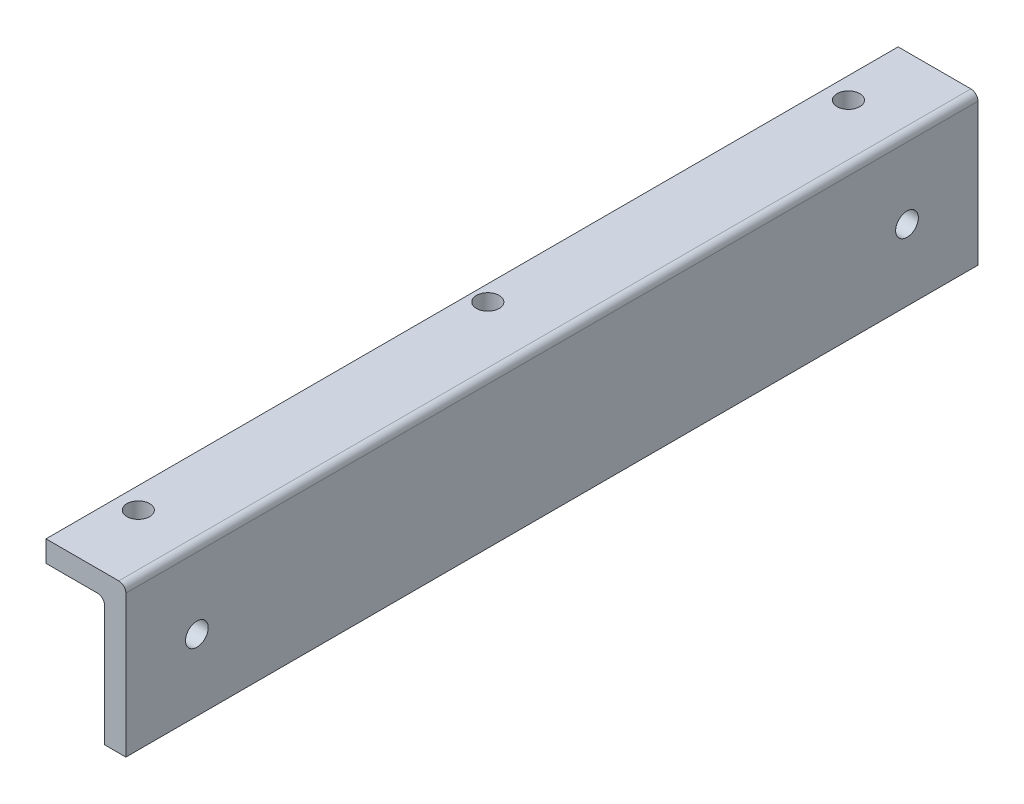
SolidWorks part; units mm, degrees
ref_plane "前视基准面" through (0, 0, 0) normal (0, 0, 1) x (1, 0, 0)
ref_plane "上视基准面" through (0, 0, 0) normal (0, 1, 0) x (1, 0, 0)
ref_plane "右视基准面" through (0, 0, 0) normal (1, 0, 0) x (0, 0, -1)
sketch "草图1" plane through (0, 0, 0) normal (0, 0, 1) x (1, 0, 0)
  line L0 (-13.7449, -0.7624) -> (-13.7449, 20.2376)
  line L1 (-13.7449, 20.2376) -> (-24.9949, 20.2376)
  line L2 (-24.9949, 20.2376) -> (-24.9949, 17.2376)
  line L3 (-24.9949, 17.2376) -> (-16.7449, 17.2376)
  line L4 (-16.7449, 17.2376) -> (-16.7449, -0.7624)
  line L5 (-16.7449, -0.7624) -> (-13.7449, -0.7624)
  dimension "D1" = 3
  dimension "D2" = 3
  dimension "D3" = 11.25
extrude "凸台-拉伸1" add sketch "草图1" along normal mid plane 120
fillet "圆角2" radius 1 1 edges at (-13.7449, 20.2376, 0)
fillet "圆角3" radius 1 1 edges at (-16.7449, 17.2376, 0)
sketch "草图6" plane through (-16.7449, 0, 0) normal (-1, 0, 0) x (0, 0, 1)
  line L0 (-60, 16.2376) -> (-60, -0.7624) construction
  line L1 (60, 16.2376) -> (60, -0.7624) construction
  circle A0 centre (50, 9.2376) radius 1.6
  circle A1 centre (-50, 9.2376) radius 1.6
  dimension "D1" = 3.2
  dimension "D3" = 3.2
  dimension "D2" = 10
  dimension "D4" = 10
extrude "切除-拉伸3" cut sketch "草图6" against normal blind 10
sketch "草图7" plane through (0, 17.2376, 0) normal (0, -1, 0) x (1, 0, 0)
  line L0 (-24.9949, -60) -> (-17.7449, -60) construction
  line L1 (-24.9949, 60) -> (-24.9949, -60) construction
  line L2 (-24.9949, 60) -> (-17.7449, 60) construction
  circle A0 centre (-21.9949, -50) radius 1.6
  circle A1 centre (-21.9949, 50) radius 1.6
  circle A2 centre (-22.7777, 0) radius 1.6
  circle A3 centre (-6.138, 23.4245) radius 3.8794
  dimension "D1" = 3.2
  dimension "D4" = 10
  dimension "D6" = 3.2
  dimension "D7" = 3.2
  dimension "D2" = 10
  dimension "D3" = 3
  dimension "D5" = 3
extrude "切除-拉伸4" cut sketch "草图7" against normal blind 10
